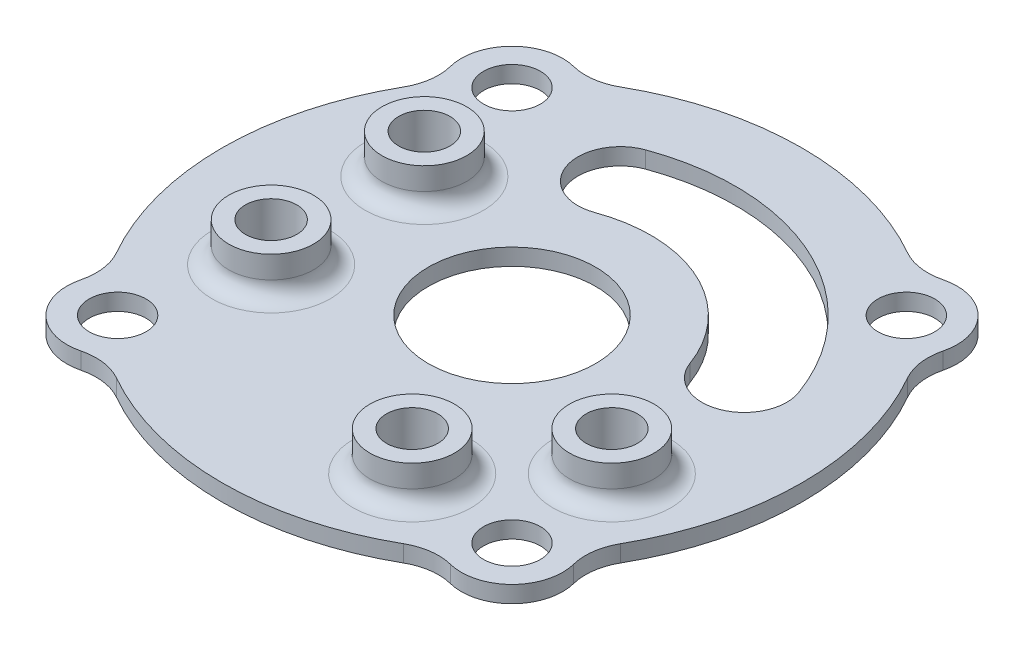
SolidWorks part; units mm, degrees
ref_plane "Front Plane" through (0, 0, 0) normal (0, 0, 1) x (1, 0, 0)
ref_plane "Top Plane" through (0, 0, 0) normal (0, 1, 0) x (1, 0, 0)
ref_plane "Right Plane" through (0, 0, 0) normal (1, 0, 0) x (0, 0, -1)
sketch "Sketch1" plane through (0, 0, 0) normal (0, 1, 0) x (1, 0, 0)
  line L0 (0, 0) -> (15.6369, -33.5334) construction
  line L1 (-35.3553, -35.3553) -> (35.3553, -35.3553) construction
  line L2 (-35.3553, -35.3553) -> (-35.3553, 35.3553) construction
  line L3 (-35.3553, 35.3553) -> (35.3553, 35.3553) construction
  line L4 (35.3553, -35.3553) -> (35.3553, 35.3553) construction
  line L5 (-35.3553, -35.3553) -> (35.3553, 35.3553) construction
  line L6 (-35.3553, 35.3553) -> (35.3553, -35.3553) construction
  line L7 (0, 0) -> (33.5334, -15.6369) construction
  line L8 (0, 0) -> (-29.455, 13.7351) construction
  line L9 (0, 0) -> (-29.455, -13.7351) construction
  circle A0 centre (0, 0) radius 52
  circle A1 centre (0, 0) radius 50 construction
  circle A2 centre (0, 0) radius 48
  circle A3 centre (35.3553, 35.3553) radius 9.1
  circle A4 centre (-35.3553, 35.3553) radius 9.1
  circle A5 centre (35.3553, -35.3553) radius 9.1
  circle A6 centre (-35.3553, -35.3553) radius 9.1
  circle A7 centre (-35.3553, 35.3553) radius 5.1
  circle A8 centre (35.3553, 35.3553) radius 5.1
  circle A9 centre (35.3553, -35.3553) radius 5.1
  circle A10 centre (-35.3553, -35.3553) radius 5.1
  circle A11 centre (0, 0) radius 37 construction
  circle A12 centre (33.5334, -15.6369) radius 4.6
  circle A13 centre (15.6369, -33.5334) radius 4.6
  circle A14 centre (0, 0) radius 32.5 construction
  circle A15 centre (-29.455, 13.7351) radius 4.6
  circle A16 centre (-29.455, -13.7351) radius 4.6
  dimension "D1" = 96
  dimension "D2" = 100
  dimension "D3" = 104
  dimension "D4" = 18.2
  dimension "D5" = 18.2
  dimension "D6" = 18.2
  dimension "D7" = 18.2
  dimension "D8" = 10.2
  dimension "D9" = 10.2
  dimension "D10" = 10.2
  dimension "D11" = 10.2
  dimension "D12" = 74
  dimension "D15" = 9.2
  dimension "D16" = 9.2
  dimension "D17" = 65
  dimension "D20" = 9.2
  dimension "D21" = 9.2
  dimension "D13" = 20
  dimension "D14" = 20
  dimension "D18" = 20
  dimension "D19" = 20
extrude "Boss-Extrude1" add sketch "Sketch1" along normal blind 3 contours A6 A2 A5 A3 A4 A16 A15 A13 A12 | A5 A0 A3 A2 | A9 A2 A5 | A9 A0 A5 A2 | A9 A0 A5 | A9 A2 A5 A0 | A6 A0 A5 A2 | A10 A2 A6 | A10 A2 A6 A0 | A10 A0 A6 | A10 A0 A6 A2 | A6 A2 A4 A0 | A7 A0 A4 | A7 A2 A4 A0 | A7 A2 A4 | A4 A2 A3 A0 | A7 A0 A4 A2 | A8 A2 A3 A0 | A8 A2 A3 | A8 A0 A3 A2 | A8 A0 A3
sketch "Sketch2" plane through (0, 3, 0) normal (0, 1, 0) x (1, 0, 0)
  circle A0 centre (-29.455, 13.7351) radius 7.6
  circle A1 centre (-29.455, 13.7351) radius 4.6
  circle A2 centre (-29.455, -13.7351) radius 4.6
  circle A3 centre (-29.455, -13.7351) radius 7.6
  circle A4 centre (15.6369, -33.5334) radius 7.6
  circle A5 centre (33.5334, -15.6369) radius 7.6
  circle A6 centre (33.5334, -15.6369) radius 4.6
  circle A7 centre (15.6369, -33.5334) radius 4.6
  dimension "D1" = 15.2
  dimension "D2" = 15.2
  dimension "D3" = 15.2
  dimension "D4" = 15.2
extrude "Boss-Extrude2" add sketch "Sketch2" along normal blind 7
fillet "Fillet1" radius 10 8 edges at (29.8349, 1.5, -42.5896) (42.5896, 1.5, -29.8349) (42.5896, 1.5, 29.8349) (29.8349, 1.5, 42.5896) (-29.8349, 1.5, 42.5896) (-42.5896, 1.5, 29.8349) (-42.5896, 1.5, -29.8349) (-29.8349, 1.5, -42.5896)
fillet "Fillet2" radius 3 4 edges at (-29.455, 3, -6.1351) (-29.455, 3, 21.3351) (15.6369, 3, 41.1334) (33.5334, 3, 23.2369)
sketch "Sketch3" plane through (0, 3, 0) normal (0, 1, 0) x (1, 0, 0)
  circle A0 centre (0, 0) radius 15
  dimension "D1" = 30
extrude "Cut-Extrude1" cut sketch "Sketch3" against normal blind 7
sketch "Sketch4" plane through (0, 3, 0) normal (0, 1, 0) x (1, 0, 0)
  line L0 (-11.1157, 30.54) -> (0, 0)
  line L1 (0, 0) -> (0, 55.6939)
  line L2 (0, 0) -> (30.54, 11.1157)
  arc A0 (-11.1157, 30.54) -> (30.54, 11.1157) centre (0, 0) cw construction
  arc A1 (37.6817, 13.715) -> (-13.715, 37.6817) centre (0, 0) ccw
  arc A2 (23.3983, 8.5163) -> (-8.5163, 23.3983) centre (0, 0) ccw
  arc A3 (23.3983, 8.5163) -> (37.6817, 13.715) centre (30.54, 11.1157) ccw
  arc A4 (-13.715, 37.6817) -> (-8.5163, 23.3983) centre (-11.1157, 30.54) ccw
  point P4 (13.7351, 29.455)
  dimension "D1" = 7.6
  dimension "D2" = 32.5
  dimension "D3" = 20
  dimension "D4" = 70
extrude "Cut-Extrude2" cut sketch "Sketch4" against normal blind 7
